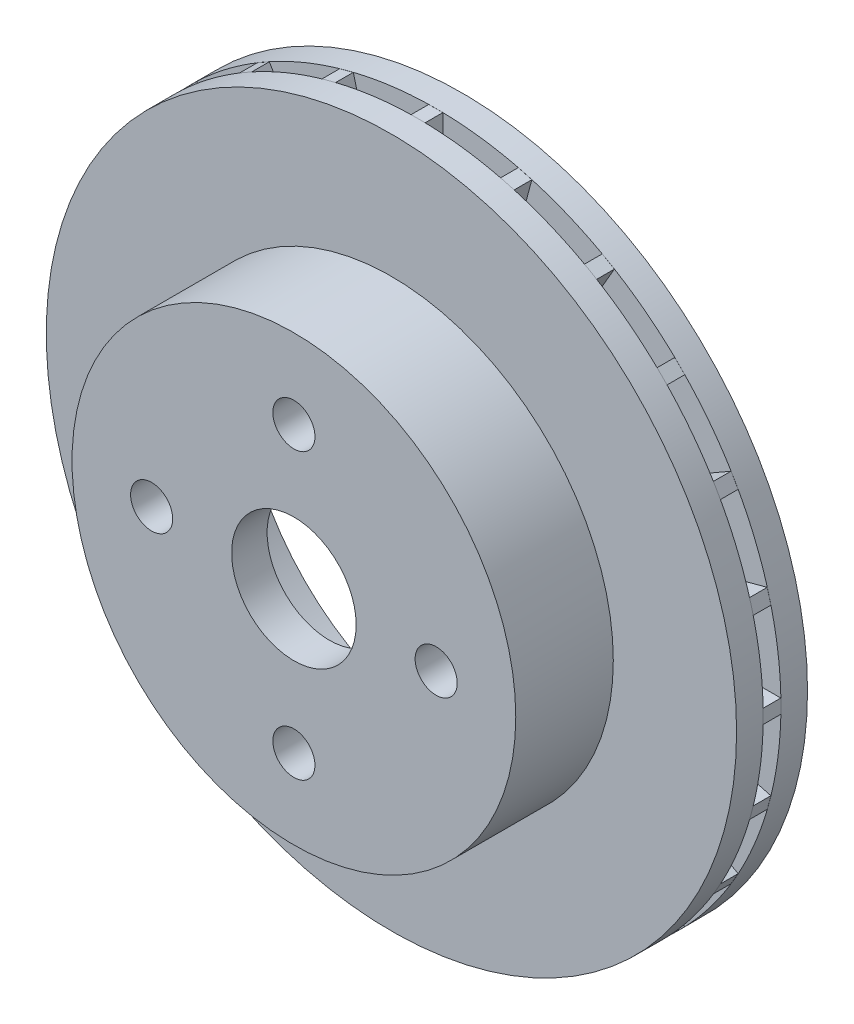
SolidWorks part; units mm, degrees
ref_plane "Front Plane" through (0, 0, 0) normal (0, 0, 1) x (1, 0, 0)
ref_plane "Top Plane" through (0, 0, 0) normal (0, 1, 0) x (1, 0, 0)
ref_plane "Right Plane" through (0, 0, 0) normal (1, 0, 0) x (0, 0, -1)
sketch "Sketch1" plane through (0, 0, 0) normal (0, 0, 1) x (1, 0, 0)
  circle A0 centre (0, 0) radius 38.9281
  circle A1 centre (0, 0) radius 25.0224
extrude "Extrude1" add sketch "Sketch1" along normal blind 3
sketch "Sketch2" plane through (0, 0, 3) normal (0, 0, 1) x (1, 0, 0)
  line L1 (25.0161, 0.7939) -> (38.9146, 0.7939)
  line L2 (25.0161, 0.7939) -> (25.0161, -0.7939)
  line L3 (25.0161, -0.7939) -> (38.9146, -0.7939)
  line L4 (38.9146, 0.7939) -> (38.9146, -0.7939)
  point P4 (25.0161, 0)
extrude "Extrude2" add sketch "Sketch2" along normal blind 2
pattern_circular "CirPattern1" count 24 over 360 about axis through (0, 0, 0) along (0, 0, 1) of "Extrude2"
pattern_linear "LPattern1" count 2 spacing 5 along (0, 0, 1) of "Extrude1"
sketch "Sketch3" plane through (0, 0, 8) normal (0, 0, 1) x (1, 0, 0)
  circle A0 centre (0, 0) radius 25.0224 construction
  circle A1 centre (0, 0) radius 25.0224
  circle A2 centre (0, 0) radius 22.0224
  dimension "D1" = 3
extrude "Extrude3" add sketch "Sketch3" along normal blind 11 and the other way up to vertex
sketch "Sketch4" plane through (0, 0, 19) normal (0, 0, 1) x (1, 0, 0)
  circle A0 centre (0, 0) radius 22.0224 construction
  circle A1 centre (0, 0) radius 22.0224
  circle A2 centre (0, 0) radius 7.0224
  dimension "D1" = 15
extrude "Extrude4" add sketch "Sketch4" against normal blind 4
sketch "Sketch5" plane through (0, 0, 19) normal (0, 0, 1) x (1, 0, 0)
  circle A0 centre (0, 16.0455) radius 2.3744
extrude "Cut-Extrude1" cut sketch "Sketch5" against normal blind 4
pattern_circular "CirPattern2" count 4 over 360 about axis through (0, 0, 0) along (0, 0, 1) of "Cut-Extrude1"
